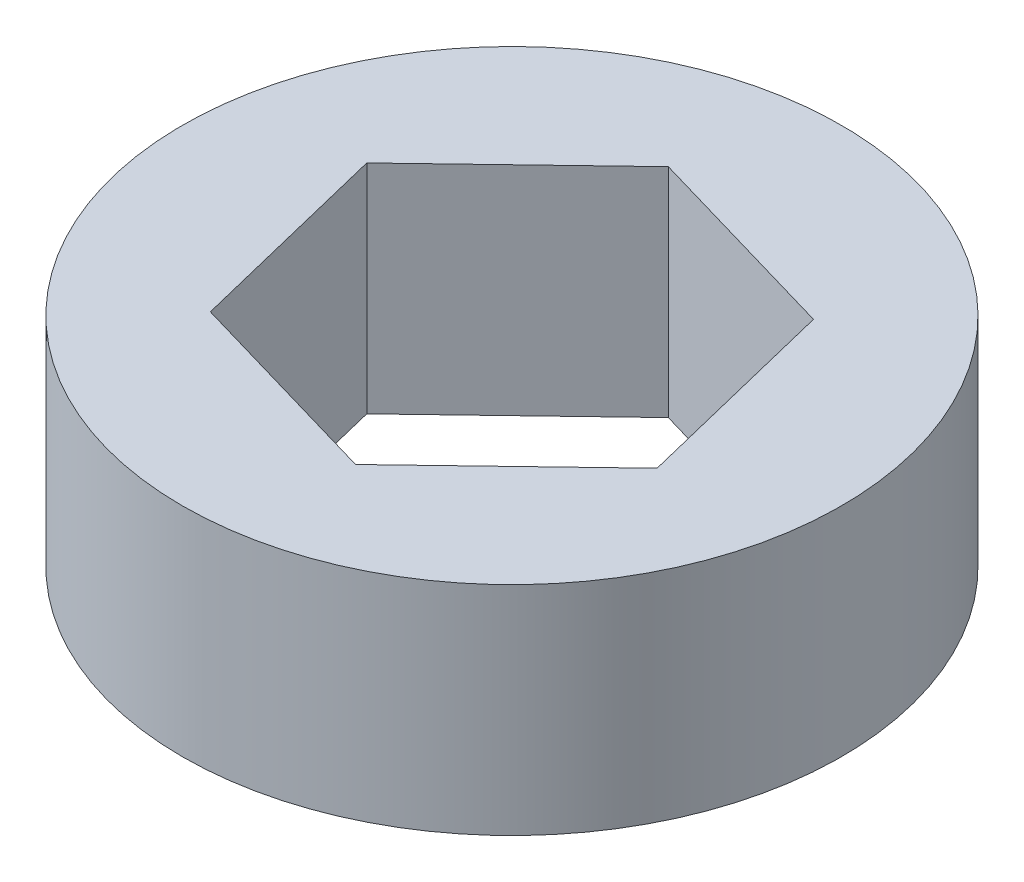
SolidWorks part; units mm, degrees
ref_plane "Front" through (0, 0, 0) normal (0, 0, 1) x (1, 0, 0)
ref_plane "Top" through (0, 0, 0) normal (0, 1, 0) x (1, 0, 0)
ref_plane "Right" through (0, 0, 0) normal (1, 0, 0) x (0, 0, -1)
sketch "Sketch1" plane through (0, 0, 0) normal (0, 1, 0) x (1, 0, 0)
  circle A0 centre (0, 0) radius 4.55
extrude "Boss-Extrude1" add sketch "Sketch1" along normal blind 3
sketch "Sketch2" plane through (0, 3, 0) normal (0, 1, 0) x (1, 0, 0)
  line L1 (-2.1264, -2.0368) -> (0.7008, -2.8599)
  line L2 (0.7008, -2.8599) -> (2.8271, -0.8231)
  line L3 (2.8271, -0.8231) -> (2.1264, 2.0368)
  line L4 (2.1264, 2.0368) -> (-0.7008, 2.8599)
  line L5 (-0.7008, 2.8599) -> (-2.8271, 0.8231)
  line L6 (-2.8271, 0.8231) -> (-2.1264, -2.0368)
  circle A0 centre (0, 0) radius 2.55 construction
  dimension "D1" = 5.1
extrude "Cut-Extrude1" cut sketch "Sketch2" against normal blind 15
